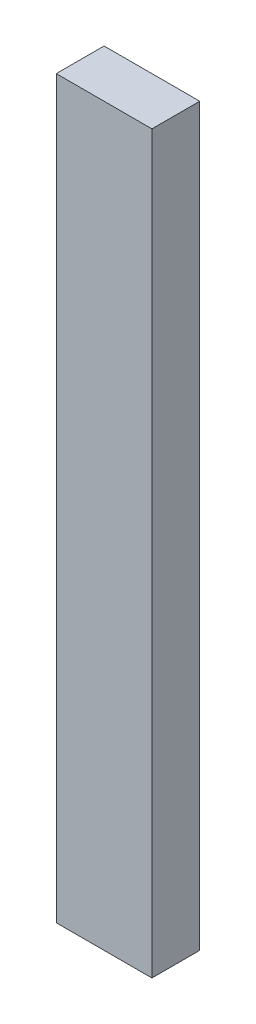
SolidWorks part; units mm, degrees
material "ABS PC"
ref_plane "Front Plane" through (0, 0, 0) normal (0, 0, 1) x (1, 0, 0)
ref_plane "Top Plane" through (0, 0, 0) normal (0, 1, 0) x (1, 0, 0)
ref_plane "Right Plane" through (0, 0, 0) normal (1, 0, 0) x (0, 0, -1)
sketch "Sketch1" plane through (0, 0, 0) normal (0, 1, 0) x (1, 0, 0)
  line L1 (0, 0) -> (25.4, 0)
  line L2 (0, 0) -> (0, 12.7)
  line L3 (0, 12.7) -> (25.4, 12.7)
  line L4 (25.4, 0) -> (25.4, 12.7)
  dimension "D1" = 25.4
  dimension "D2" = 12.7
extrude "Boss-Extrude1" add sketch "Sketch1" along normal blind 195.2625
